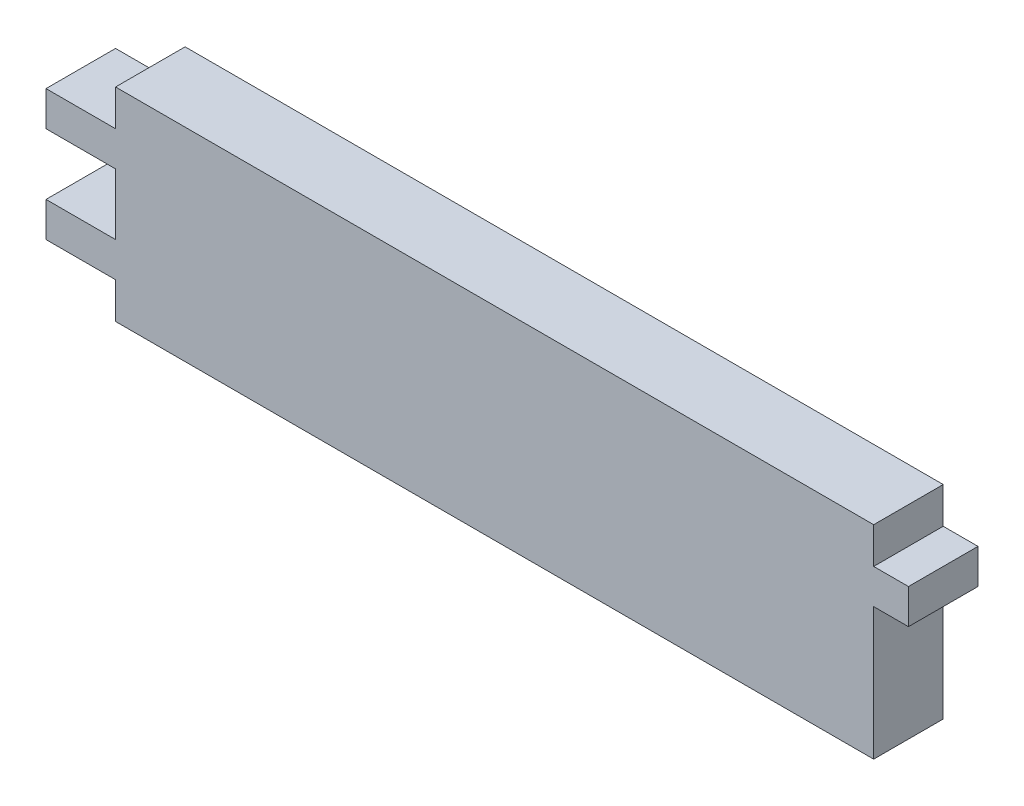
SolidWorks part; units mm, degrees
material "Balsa"
ref_plane "Front Plane" through (0, 0, 0) normal (0, 0, 1) x (1, 0, 0)
ref_plane "Top Plane" through (0, 0, 0) normal (0, 1, 0) x (1, 0, 0)
ref_plane "Right Plane" through (0, 0, 0) normal (1, 0, 0) x (0, 0, -1)
sketch "Sketch1" plane through (0, 0, 0) normal (0, 0, 1) x (1, 0, 0)
  line L0 (-75.8404, 8.2417) -> (-69.4904, 8.2417)
  line L1 (-75.8404, 8.2417) -> (-75.8404, 5.0667)
  line L2 (-75.8404, 5.0667) -> (-69.4904, 5.0667)
  line L3 (-69.4904, 5.0667) -> (-69.4904, -0.5213)
  line L4 (-69.4904, -0.5213) -> (-75.8404, -0.5213)
  line L5 (-75.8404, -0.5213) -> (-75.8404, -3.6963)
  line L6 (-75.8404, -3.6963) -> (-69.4904, -3.6963)
  line L7 (-69.4904, 15.3554) -> (-69.4904, -12.0155) construction
  line L8 (-69.4904, 8.2417) -> (-69.4904, 11.5437)
  line L9 (-0.2754, 5.0667) -> (2.8996, 5.0667)
  line L10 (2.8996, 5.0667) -> (2.8996, 8.2417)
  line L11 (2.8996, 8.2417) -> (-0.2754, 8.2417)
  line L12 (-0.2754, 8.2417) -> (-0.2754, 11.5437)
  line L13 (-0.2754, 11.5437) -> (-69.4904, 11.5437)
  line L14 (-0.2754, 5.0667) -> (-0.2754, -6.9983)
  line L16 (-69.4904, -6.9983) -> (-69.4904, -3.6963)
  line L18 (-69.4904, -6.9983) -> (-0.2754, -6.9983)
  point P18 (-69.4904, 2.2727)
  point P19 (-69.4904, -6.9983)
  point P21 (-69.4904, 11.5437)
  dimension "D1" = 9.271
  dimension "D2" = 9.271
extrude "Boss-Extrude1" add sketch "Sketch1" along normal up to surface (6.35 mm away)
